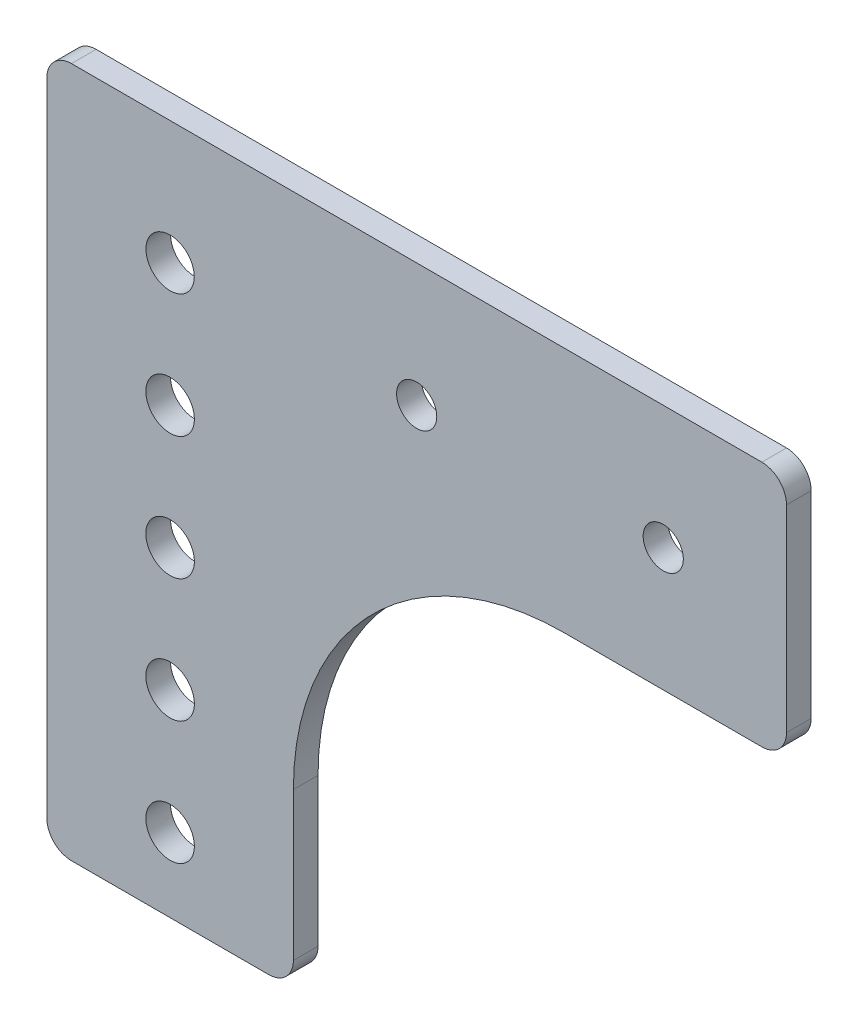
SolidWorks part; units mm, degrees
ref_plane "Front Plane" through (0, 0, 0) normal (0, 0, 1) x (1, 0, 0)
ref_plane "Top Plane" through (0, 0, 0) normal (0, 1, 0) x (1, 0, 0)
ref_plane "Right Plane" through (0, 0, 0) normal (1, 0, 0) x (0, 0, -1)
sketch "Sketch1" plane through (0, 0, 0) normal (0, 0, 1) x (1, 0, 0)
  line L2 (85.66, -50.8) -> (65.34, -50.8)
  line L3 (88.2, -48.26) -> (88.2, -27.94)
  line L4 (85.66, -25.4) -> (14.54, -25.4)
  line L5 (12, -50.8) -> (12, -27.94)
  line L6 (34.86, -96.52) -> (14.54, -96.52)
  line L7 (37.4, -93.98) -> (37.4, -78.74)
  line L9 (12, -93.98) -> (12, -50.8)
  arc A0 (14.54, -96.52) -> (12, -93.98) centre (14.54, -93.98) cw
  arc A1 (34.86, -96.52) -> (37.4, -93.98) centre (34.86, -93.98) ccw
  arc A2 (85.66, -50.8) -> (88.2, -48.26) centre (85.66, -48.26) ccw
  arc A3 (88.2, -27.94) -> (85.66, -25.4) centre (85.66, -27.94) ccw
  arc A4 (14.54, -25.4) -> (12, -27.94) centre (14.54, -27.94) ccw
  arc A5 (37.4, -78.74) -> (65.34, -50.8) centre (65.34, -78.74) cw
  circle A6 centre (24.7, -88.9) radius 2.5
  circle A7 centre (24.7, -76.2) radius 2.5
  circle A8 centre (24.7, -63.5) radius 2.5
  circle A9 centre (24.7, -50.8) radius 2.5
  circle A10 centre (24.7, -38.1) radius 2.4892
  circle A11 centre (50.1, -38.1) radius 2.0701
  circle A12 centre (75.5, -38.1) radius 2.0701
  dimension "D4" = 2.54
  dimension "D5" = 27.94
  dimension "D6" = 5
  dimension "D7" = 4.1402
  dimension "D8" = 4.1402
  dimension "D9" = 4.9784
  dimension "D10" = 5
  dimension "D11" = 5
  dimension "D12" = 5
extrude "Boss-Extrude1" add sketch "Sketch1" along normal blind 2.54
